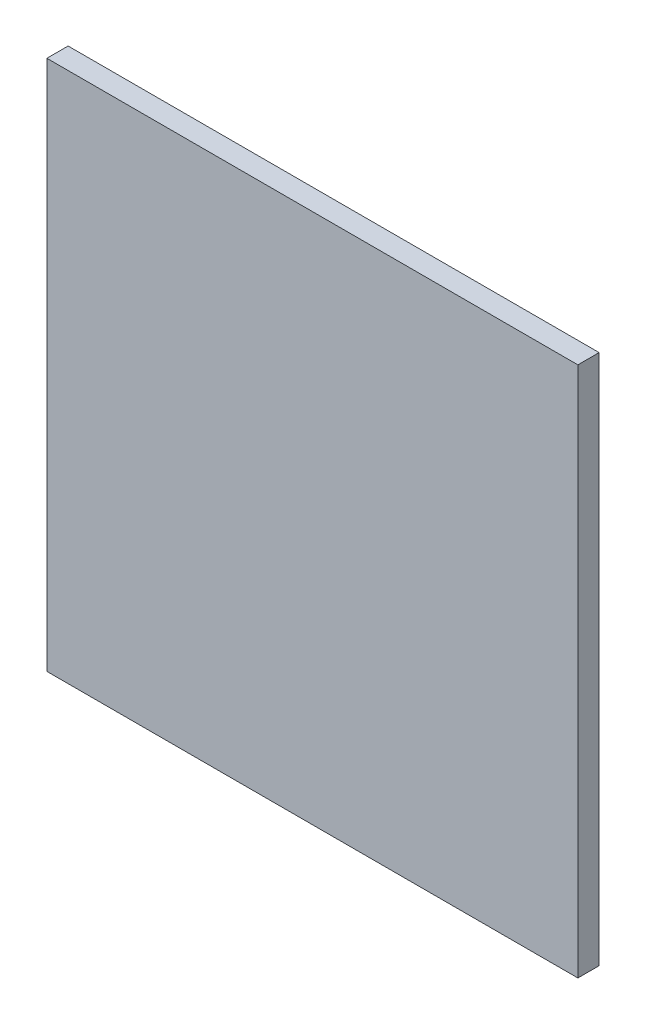
SolidWorks part; units mm, degrees
ref_plane "Front Plane" through (0, 0, 0) normal (0, 0, 1) x (1, 0, 0)
ref_plane "Top Plane" through (0, 0, 0) normal (0, 1, 0) x (1, 0, 0)
ref_plane "Right Plane" through (0, 0, 0) normal (1, 0, 0) x (0, 0, -1)
sketch "Sketch1" plane through (0, 0, 0) normal (0, 0, 1) x (1, 0, 0)
  line L1 (-37.5, -37.5) -> (37.5, -37.5)
  line L2 (-37.5, -37.5) -> (-37.5, 37.5)
  line L3 (-37.5, 37.5) -> (37.5, 37.5)
  line L4 (37.5, -37.5) -> (37.5, 37.5)
  line L5 (0, 37.5) -> (0, -37.5) construction
  line L6 (-37.5, 0) -> (37.5, 0) construction
  point P0 (0, 0)
  dimension "D1" = 75
  dimension "D2" = 75
extrude "Boss-Extrude1" add sketch "Sketch1" along normal blind 3
